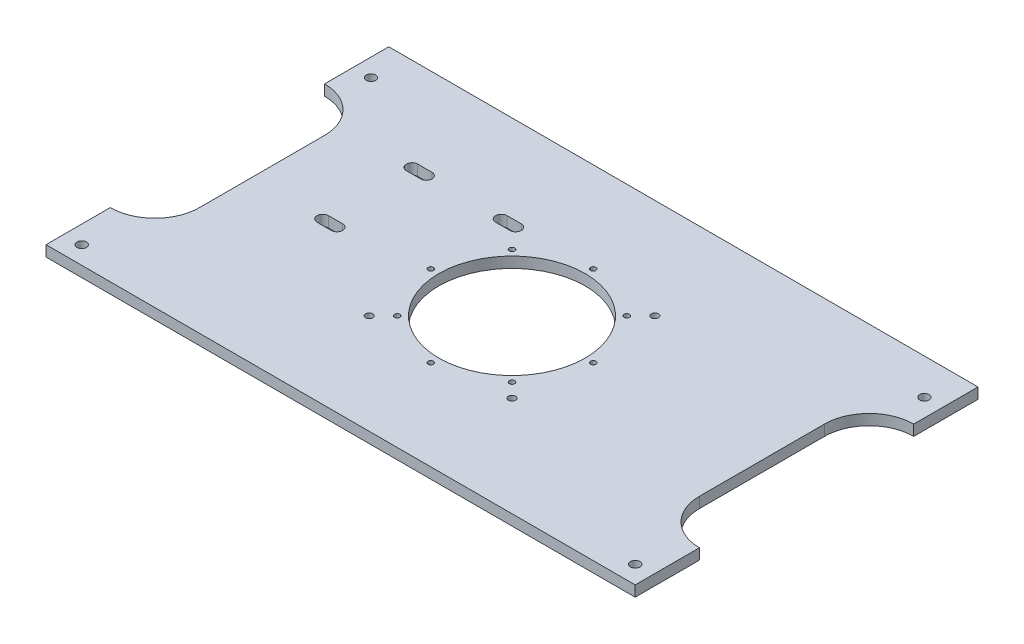
SolidWorks part; units mm, degrees
material "6061 Alloy"
ref_plane "Front Plane" through (0, 0, 0) normal (0, 0, 1) x (1, 0, 0)
ref_plane "Top Plane" through (0, 0, 0) normal (0, 1, 0) x (1, 0, 0)
ref_plane "Right Plane" through (0, 0, 0) normal (1, 0, 0) x (0, 0, -1)
sketch "Sketch1" plane through (0, 0, 0) normal (0, 1, 0) x (1, 0, 0)
  line L1 (0, 0) -> (330, 0)
  line L2 (0, 0) -> (0, 192)
  line L3 (0, 192) -> (330, 192)
  line L4 (330, 0) -> (330, 192)
  dimension "D1" = 192
  dimension "D2" = 330
extrude "Boss-Extrude1" add sketch "Sketch1" along normal blind 6
sketch "Sketch2" plane through (0, 6, 0) normal (0, 1, 0) x (1, 0, 0)
  line L0 (0, 0) -> (330, 0) construction
  line L1 (0, 0) -> (0, 192)
  circle A0 centre (165, 96) radius 50 construction
  circle A1 centre (165, 96) radius 45.5 construction
  circle A2 centre (165, 141.5) radius 1.5
  circle A3 centre (197.1734, 128.1734) radius 1.5
  circle A4 centre (210.5, 96) radius 1.5
  circle A5 centre (197.1734, 63.8266) radius 1.5
  circle A6 centre (165, 50.5) radius 1.5
  circle A7 centre (132.8266, 63.8266) radius 1.5
  circle A8 centre (119.5, 96) radius 1.5
  circle A9 centre (132.8266, 128.1734) radius 1.5
  point P21 (165, 96)
  dimension "D1" = 100
  dimension "D2" = 91
  dimension "D3" = 3
  dimension "D5" = 192
  dimension "D6" = 330
  dimension "D4" = 8
extrude "Cut-Extrude1" cut sketch "Sketch2" against normal through all and the other way through all contours A2 | A3 | A4 | A6 | A7 | A8 | A9 | A5
sketch "Sketch3" plane through (0, 6, 0) normal (0, 1, 0) x (1, 0, 0)
  line L0 (0, 0) -> (0, 192)
  line L1 (0, 0) -> (330, 0)
  line L2 (0, 0) -> (330, 0) construction
  circle A0 centre (165, 96) radius 41
  dimension "D1" = 82
  dimension "D2" = 330
  dimension "D3" = 192
extrude "Cut-Extrude2" cut sketch "Sketch3" against normal through all contours A0
sketch "Sketch4" plane through (0, 6, 0) normal (0, 1, 0) x (1, 0, 0)
  line L0 (165, 96) -> (208.759, 133.3015) construction
  line L1 (165, 96) -> (165, 153.5) construction
  line L2 (165, 96) -> (187.0043, 149.1231) construction
  circle A0 centre (165, 96) radius 57.5 construction
  circle A1 centre (187.0043, 149.1231) radius 3
  circle A2 centre (224.1231, 73.9957) radius 3
  circle A3 centre (148.9957, 36.8769) radius 3
  circle A4 centre (111.8769, 112.0043) radius 3
  point P16 (168, 93)
  dimension "D1" = 115
  dimension "D2" = 22.5
  dimension "D3" = 6
  dimension "D4" = 4
extrude "Cut-Extrude3" [suppressed] cut sketch "Sketch4" against normal blind 10
sketch "Sketch7" plane through (0, 0, 0) normal (0, -1, 0) x (1, 0, 0)
  line L0 (0, 0) -> (0, -115) construction
  line L1 (0, -192) -> (0, 0) construction
  line L2 (0, -115) -> (93, -115) construction
  circle A0 centre (93, -115) radius 3
  dimension "D3" = 6
  dimension "D1" = 115
  dimension "D2" = 93
extrude "Cut-Extrude4" [suppressed] cut sketch "Sketch7" against normal blind 10
hole_wizard "Tap Drill for M6 Helicoil1" [suppressed] positions "Sketch8" profile "Sketch9" hole size "M6x1.0" standard "DIN"
sketch "Sketch8" [suppressed] plane through (0, 0, 0) normal (0, -1, 0) x (-1, 0, 0)
  line L1 (-63, 85) -> (-123, 85)
  line L2 (-63, 85) -> (-63, 145)
  line L3 (-63, 145) -> (-123, 145)
  line L4 (-123, 85) -> (-123, 145)
  line L5 (-63, 85) -> (-123, 145) construction
  line L6 (-63, 145) -> (-123, 85) construction
  point P1 (-93, 115)
  dimension "D1" = 60
sketch "Sketch9" plane through (93, 0, -115) normal (1, 0, 0) x (0, 0, -1)
  line L0 (0, 0) -> (0, 13.8177)
  line L1 (0, 13.8177) -> (3.125, 11.94)
  line L2 (3.125, 11.94) -> (3.125, 0)
  line L5 (3.125, 0) -> (0, 0)
  line L10 (0, 13.8177) -> (-3.125, 11.94) construction
  line L11 (0, -6.35) -> (0, 107.95) construction
  dimension "Hole Dia." = 6.25
  dimension "Hole Depth" = 11.94
  dimension "Drill Angle" = 118
sketch "Sketch10" plane through (0, 0, 0) normal (0, -1, 0) x (1, 0, 0)
  line L0 (330, -192) -> (0, -192) construction
  line L1 (123, -140) -> (73, -140) construction
  line L2 (123, -140) -> (123, -90) construction
  line L3 (123, -90) -> (73, -90) construction
  line L4 (73, -140) -> (73, -90) construction
  line L5 (123, -140) -> (73, -90) construction
  line L6 (123, -90) -> (73, -140) construction
  line L7 (0, -192) -> (0, 0) construction
  line L8 (73, -90) -> (65, -90) construction
  line L9 (73, -93.2) -> (65, -93.2)
  line L10 (73, -86.8) -> (65, -86.8)
  line L11 (73, -140) -> (65, -140) construction
  line L12 (73, -143.2) -> (65, -143.2)
  line L13 (73, -136.8) -> (65, -136.8)
  line L14 (123, -140) -> (115, -140) construction
  line L15 (123, -143.2) -> (115, -143.2)
  line L16 (123, -136.8) -> (115, -136.8)
  arc A0 (73, -93.2) -> (73, -86.8) centre (73, -90) ccw
  arc A1 (73, -143.2) -> (73, -136.8) centre (73, -140) ccw
  arc A2 (123, -143.2) -> (123, -136.8) centre (123, -140) ccw
  arc A3 (73, -93.2) -> (73, -86.8) centre (73, -90) ccw
  arc A4 (65, -86.8) -> (65, -93.2) centre (65, -90) ccw
  arc A5 (73, -143.2) -> (73, -136.8) centre (73, -140) ccw
  arc A6 (65, -136.8) -> (65, -143.2) centre (65, -140) ccw
  arc A7 (123, -143.2) -> (123, -136.8) centre (123, -140) ccw
  arc A8 (115, -136.8) -> (115, -143.2) centre (115, -140) ccw
  point P0 (98, -115)
  point P13 (69, -90)
  point P19 (69, -140)
  point P25 (119, -140)
  point P37 (98, -115)
  dimension "D2" = 6.4
  dimension "D3" = 6.4
  dimension "D4" = 6.4
  dimension "D5" = 77
  dimension "D6" = 98
  dimension "D7" = 8
extrude "Cut-Extrude5" cut sketch "Sketch10" against normal blind 10 contours L16 A8 L15 A2 | L13 A6 L12 A1 | L10 A4 L9 A0
sketch "Sketch11" plane through (0, 0, 0) normal (0, -1, 0) x (1, 0, 0)
  line L5 (125, -136) -> (205, -136) construction
  line L11 (125, -136) -> (125, -56) construction
  line L12 (125, -56) -> (205, -56) construction
  line L13 (205, -136) -> (205, -56) construction
  line L14 (125, -136) -> (205, -56)
  line L15 (125, -56) -> (205, -136)
  circle A4 centre (125, -56) radius 2
  circle A5 centre (205, -56) radius 2
  circle A6 centre (205, -136) radius 2
  point P0 (165, -96)
  dimension "D3" = 4
  dimension "D1" = 80
  dimension "D2" = 80
extrude "Cut-Extrude6" cut sketch "Sketch11" against normal blind 10
hole_wizard "M5 Clearance Hole1" positions "Sketch13" profile "Sketch14" hole size "M5" standard "DIN"
sketch "Sketch13" plane through (0, 6, 0) normal (0, 1, 0) x (1, 0, 0)
  line L0 (0, 192) -> (0, 0) construction
  line L1 (330, 0) -> (330, 192) construction
  line L2 (10, 172) -> (320, 172) construction
  line L3 (320, 172) -> (320, 10) construction
  line L4 (320, 10) -> (10, 10) construction
  line L5 (10, 10) -> (10, 172) construction
  line L15 (330, 192) -> (0, 192) construction
  point P0 (10, 172)
  point P2 (10, 10)
  point P4 (320, 10)
  point P6 (320, 172)
  dimension "D1" = 10
  dimension "D2" = 10
  dimension "D3" = 10
  dimension "D4" = 10
  dimension "D5" = 162
  dimension "D6" = 162
  dimension "D7" = 20
sketch "Sketch14" plane through (10, 6, -172) normal (1, 0, 0) x (0, 0, 1)
  line L0 (0, 0) -> (0, 13.5323)
  line L1 (0, 13.5323) -> (2.65, 11.94)
  line L2 (2.65, 11.94) -> (2.65, 0)
  line L5 (2.65, 0) -> (0, 0)
  line L10 (0, 13.5323) -> (-2.65, 11.94) construction
  line L11 (0, -6.35) -> (0, 107.95) construction
  dimension "Hole Dia." = 5.3
  dimension "Hole Depth" = 11.94
  dimension "Drill Angle" = 118
sketch "Sketch15" [suppressed] plane through (0, 0, 0) normal (0, -1, 0) x (1, 0, 0)
  line L0 (0, 0) -> (330, 0) construction
  line L1 (0, -192) -> (10, -192)
  line L2 (0, -192) -> (0, 0)
  line L3 (0, 0) -> (10, 0)
  line L4 (10, -192) -> (10, 0)
  line L6 (330, -192) -> (320, -192)
  line L7 (330, -192) -> (330, 0)
  line L8 (330, 0) -> (320, 0)
  line L9 (320, -192) -> (320, 0)
  line L10 (10, 0) -> (320, 0)
  line L11 (10, 0) -> (10, -10)
  line L12 (10, -10) -> (320, -10)
  line L13 (320, 0) -> (320, -10)
  line L14 (320, -192) -> (10, -192)
  line L15 (320, -192) -> (320, -182)
  line L16 (320, -182) -> (10, -182)
  line L17 (10, -192) -> (10, -182)
  dimension "D1" = 10
  dimension "D2" = 10
  dimension "D3" = 10
  dimension "D4" = 10
extrude "Cut-Extrude7" [suppressed] cut sketch "Sketch15" against normal blind 0.05 contours L10 L13 L12 L11 | L4 L1 L2 L3 | L15 L16 L17 L14 | L6 L7 L8 L9
sketch "Sketch16" [suppressed] plane through (0, 6, 0) normal (0, 1, 0) x (1, 0, 0)
  circle A0 centre (165, 96) radius 41
  circle A1 centre (165, 96) radius 50
  dimension "D1" = 100
extrude "Boss-Extrude2" [suppressed] add sketch "Sketch16" along normal blind 0.05
sketch "Sketch17" [suppressed] plane through (0, 6, 0) normal (0, 1, 0) x (1, 0, 0)
  line L0 (50, 192) -> (280, 192) construction
  line L1 (330, 192) -> (0, 192) construction
  line L2 (50, 222) -> (280, 222)
  line L3 (50, 162) -> (280, 162)
  line L4 (330, 0) -> (330, 192) construction
  line L5 (0, 192) -> (0, 0) construction
  line L6 (280, 0) -> (50, 0) construction
  line L7 (0, 0) -> (330, 0) construction
  line L8 (280, -30) -> (50, -30)
  line L9 (280, 30) -> (50, 30)
  line L10 (330, 96) -> (280, 96) construction
  line L11 (330, 53.5) -> (280, 53.5)
  line L12 (330, 138.5) -> (280, 138.5)
  arc A0 (50, 222) -> (50, 162) centre (50, 192) ccw
  arc A1 (280, 162) -> (280, 222) centre (280, 192) ccw
  arc A2 (280, -30) -> (280, 30) centre (280, 0) ccw
  arc A3 (50, 30) -> (50, -30) centre (50, 0) ccw
  arc A4 (330, 53.5) -> (330, 138.5) centre (330, 96) ccw
  arc A5 (280, 138.5) -> (280, 53.5) centre (280, 96) ccw
  point P4 (165, 192)
  point P17 (165, 0)
  point P24 (305, 96)
  point P29 (305, 138.5)
  dimension "D1" = 50
  dimension "D2" = 50
  dimension "D3" = 50
  dimension "D4" = 50
  dimension "D5" = 60
  dimension "D6" = 60
  dimension "D7" = 85
  dimension "D8" = 50
extrude "Cut-Extrude8" [suppressed] cut sketch "Sketch17" against normal through all
sketch "Sketch18" [suppressed] plane through (0, 6, 0) normal (0, 1, 0) x (1, 0, 0)
  line L0 (0, 126) -> (0, 66) construction
  line L1 (0, 192) -> (0, 0) construction
  line L2 (30, 126) -> (30, 66)
  line L3 (-30, 126) -> (-30, 66)
  line L4 (0, 66) -> (0, 0) construction
  line L5 (0, 126) -> (0, 192) construction
  arc A0 (30, 126) -> (-30, 126) centre (0, 126) ccw
  arc A1 (-30, 66) -> (30, 66) centre (0, 66) ccw
  point P4 (0, 96)
  dimension "D1" = 60
  dimension "D2" = 60
extrude "Cut-Extrude9" [suppressed] cut sketch "Sketch18" against normal through all
sketch "Sketch19" plane through (0, 6, 0) normal (0, 1, 0) x (1, 0, 0)
  line L0 (0, 131) -> (0, 61) construction
  line L1 (0, 192) -> (0, 0) construction
  line L2 (25, 131) -> (25, 61)
  line L3 (-25, 131) -> (-25, 61)
  line L4 (165, 96) -> (165, 212.217) construction
  line L5 (330, 131) -> (330, 61) construction
  line L6 (305, 131) -> (305, 61)
  line L7 (355, 131) -> (355, 61)
  arc A0 (25, 131) -> (-25, 131) centre (0, 131) ccw
  arc A1 (-25, 61) -> (25, 61) centre (0, 61) ccw
  arc A2 (305, 131) -> (355, 131) centre (330, 131) cw
  arc A3 (355, 61) -> (305, 61) centre (330, 61) cw
  point P4 (0, 96)
  point P14 (330, 96)
  dimension "D1" = 70
  dimension "D2" = 50
extrude "Cut-Extrude10" cut sketch "Sketch19" against normal through all
equation "\"D2@Sketch13\"=\"D1@Sketch13\""
equation "\"D3@Sketch13\"=\"D1@Sketch13\""
equation "\"D4@Sketch13\"=\"D1@Sketch13\""
equation "\"D6@Sketch13\"=\"D5@Sketch13\""
